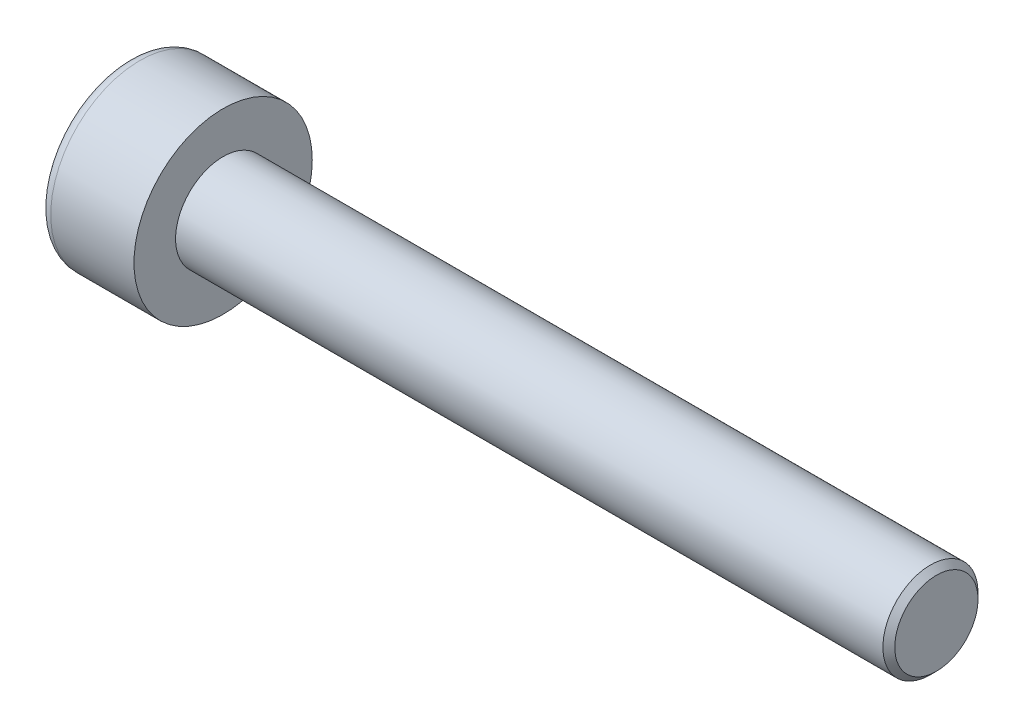
SolidWorks part; units mm, degrees
ref_plane "Front" through (0, 0, 0) normal (0, 0, 1) x (1, 0, 0)
ref_plane "Top" through (0, 0, 0) normal (0, 1, 0) x (1, 0, 0)
ref_plane "Right" through (0, 0, 0) normal (1, 0, 0) x (0, 0, -1)
sketch "Sketch1" plane through (0, 0, 0) normal (1, 0, 0) x (0, 0, -1)
  circle A0 centre (0, 0) radius 1.5
  dimension "dk" = 3
extrude "BaseHead" add sketch "Sketch1" along normal blind 1.6
sketch "Sketch2" plane through (1.6, 0, 0) normal (1, 0, 0) x (0, 0, -1)
  circle A0 centre (0, 0) radius 0.8
  dimension "d" = 1.6
extrude "BaseBody" add sketch "Sketch2" along normal blind 12
cosmetic thread "ThreadCosmetic1" parameters "b"=12, "D2"=1.221
sketch "Sketch3" plane through (0, 0, 0) normal (1, 0, 0) x (0, 0, -1)
  line L1 (0.866, 0) -> (0.433, 0.75)
  line L2 (0.433, 0.75) -> (-0.433, 0.75)
  line L3 (-0.433, 0.75) -> (-0.866, 0)
  line L4 (-0.866, 0) -> (-0.433, -0.75)
  line L5 (-0.433, -0.75) -> (0.433, -0.75)
  line L6 (0.433, -0.75) -> (0.866, 0)
  circle A0 centre (0, 0) radius 0.75 construction
  dimension "s" = 1.5
  dimension "e" = 1.7321
extrude "HexagonSocket" cut sketch "Sketch3" along normal blind 0.7
sketch "Sketch4" plane through (-4.1961, 0.75, 0) normal (0, 0, 1) x (-1, 0, 0)
  line L0 (-4.8961, 1.5) -> (-5.3292, 0.75)
  line L2 (-5.3292, 0.75) -> (-4.8961, 0.75)
  line L3 (-4.8961, 0.75) -> (-4.8961, 1.5)
  line L4 (-5.0351, 0.75) -> (0.839, 0.75) construction
  line L5 (-17.7961, 0.75) -> (-5.7961, 0.75) construction
  line L6 (-5.7961, 0.75) -> (-4.1961, 0.75) construction
  dimension "m" = 60
revolve "Cut-Revolve1" cut sketch "Sketch4" angle 360 about L4
fillet "HeadFillet" [suppressed] radius 0.1
fillet "TopFillet" radius 0.2 1 edges at (0, 0, -1.5)
chamfer "Chamfer1" distance 0.1 angle 45 1 edges at (13.6, 0, -0.8)
sketch "Sketch5" plane through (0, 0, 0) normal (0, 0, 1) x (1, 0, 0)
  line L0 (13.5, 0.6359) -> (13.5948, 0.8)
  line L1 (13.5948, 0.8) -> (13.5948, 0.9895)
  line L2 (13.5948, 0.9895) -> (13.4053, 0.9895)
  line L3 (13.4053, 0.9895) -> (13.4053, 0.8)
  line L4 (13.4053, 0.8) -> (13.5, 0.6359)
  line L5 (0, 0) -> (7.8886, 0) construction
  line L6 (13.5, -0.8) -> (13.5, 0.8) construction
  dimension "D1" = 1.6
  dimension "D2" = 0.1895
revolve "Cut-Revolve10" [suppressed] cut sketch "Sketch5" angle 360 about L5
pattern_linear "LPattern10" [suppressed] count 53 spacing 0.2274 along (1, 0, 0)
equation "\"r1@TopFillet\" = \"d@Sketch2\" / 8"
equation "\"D1@Chamfer1\" = \"r@HeadFillet\""
equation "\"D1@Sketch5\" = \"d@Sketch2\""
equation "\"D2@Sketch5\" =  ( \"d@Sketch2\" - \"D2@ThreadCosmetic1\" )  / 2"
equation "\"D3@LPattern10\" = \"D2@Sketch5\" * 1.2"
equation "\"D1@LPattern10\" = \"b@ThreadCosmetic1\" / \"D3@LPattern10\""
